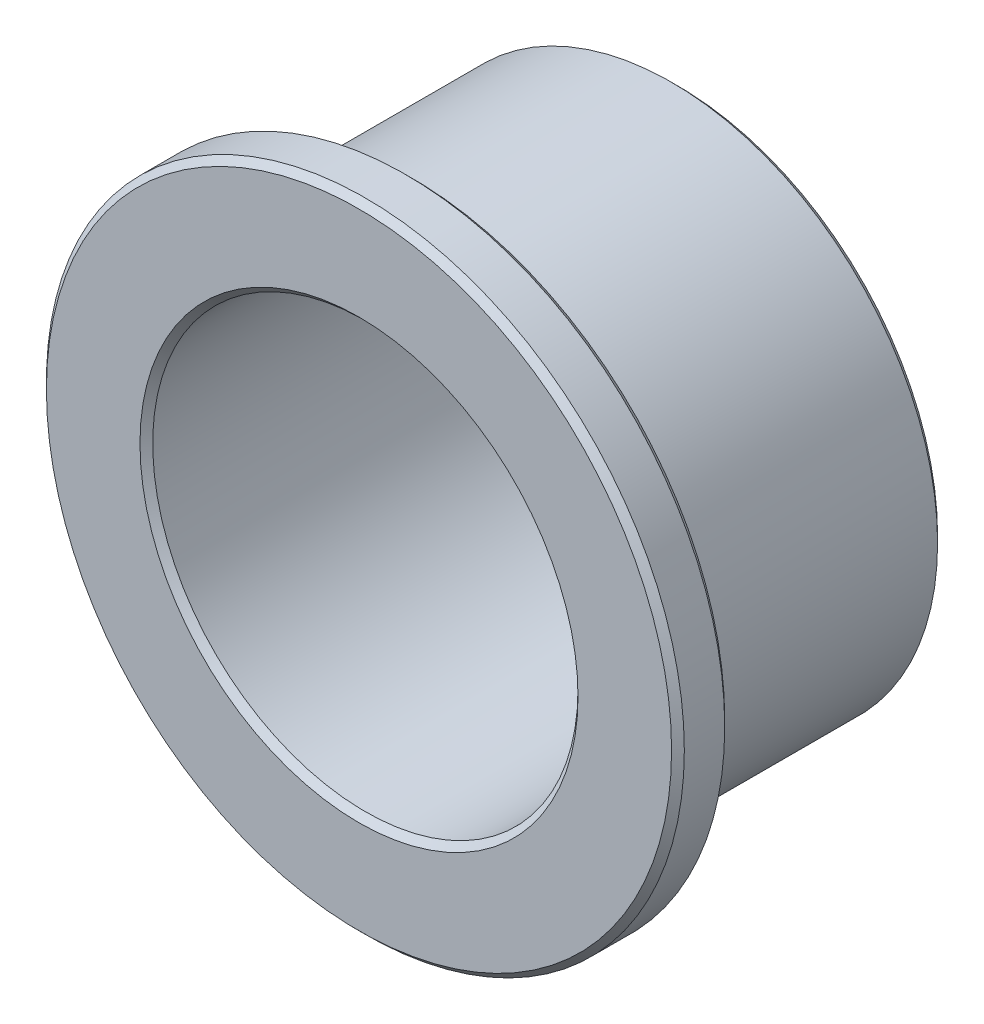
SolidWorks part; units mm, degrees
ref_plane "Front" through (0, 0, 0) normal (0, 0, 1) x (1, 0, 0)
ref_plane "Top" through (0, 0, 0) normal (0, 1, 0) x (1, 0, 0)
ref_plane "Right" through (0, 0, 0) normal (1, 0, 0) x (0, 0, -1)
sketch "Sketch1" plane through (0, 0, 0) normal (0, 0, 1) x (1, 0, 0)
  circle A0 centre (0, 0) radius 12.7
  circle A1 centre (0, 0) radius 15.8877
  circle A2 centre (0, 0) radius 19.05
  dimension "ID" = 25.4
  dimension "OD" = 31.7754
  dimension "Flange OD" = 38.1
sketch "Sketch2" plane through (0, 0, 0) normal (1, 0, 0) x (0, 0, -1)
  line L0 (-9.525, -19.05) -> (9.525, -19.05) construction
  line L1 (0, 19.05) -> (0, -19.05) construction
  line L3 (-6.35, 15.8877) -> (9.525, 15.8877) construction
  point P3 (0, -19.05)
  point P7 (0, 15.8877)
  point P9 (-6.35, -19.05)
  point P10 (-9.525, 19.05)
  point P23 (0, 19.05)
  dimension "Flange Thickness" = 3.175
  dimension "Length" = 19.05
sketch "Sketch3" plane through (0, 0, 0) normal (0, 0, 1) x (1, 0, 0)
  circle A0 centre (0, 0) radius 19.05 construction
  circle A1 centre (0, 0) radius 19.05
  circle A2 centre (0, 0) radius 12.7 construction
  circle A3 centre (0, 0) radius 12.7
extrude "Boss-Extrude1" add sketch "Sketch3" against normal up to vertex (-6.35 mm away) from vertex at 9.525 starting at point (0, -19.05, 9.525)
sketch "Sketch4" plane through (0, 0, 0) normal (0, 0, 1) x (1, 0, 0)
  circle A0 centre (0, 0) radius 12.7 construction
  circle A1 centre (0, 0) radius 15.8877 construction
  circle A2 centre (0, 0) radius 12.7
  circle A3 centre (0, 0) radius 15.8877
extrude "Boss-Extrude2" add sketch "Sketch4" against normal up to vertex (9.525 mm away) from vertex at 6.35 starting at point (0, -19.05, 6.35)
chamfer "Chamfer1" distance 0.381 angle 45 6 edges at (12.7, 0, 9.525) (19.05, 0, 9.525) (19.05, 0, 6.35) (15.8877, 0, 6.35) (12.7, 0, -9.525) (15.8877, 0, -9.525)
equation "\"D1@Chamfer1\"=\"ID@Sketch1\"*0.015"
